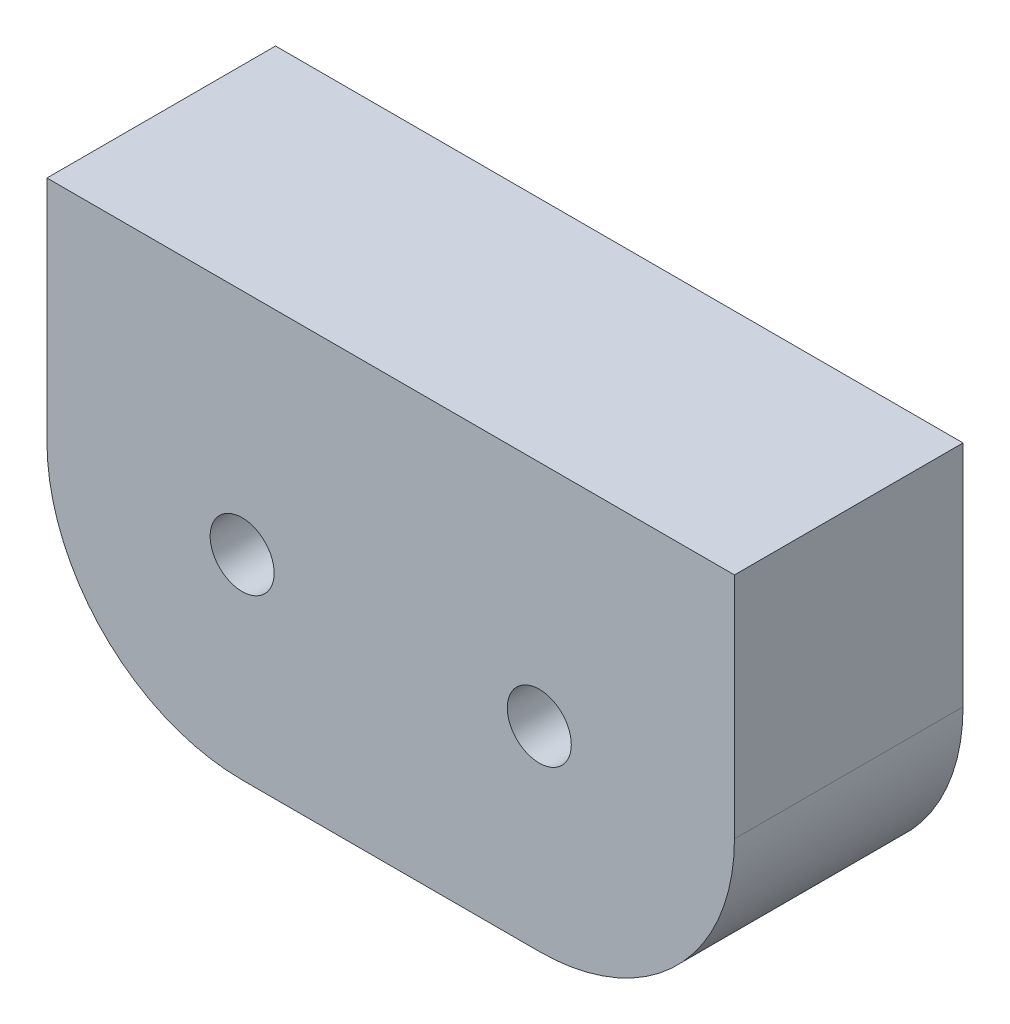
SolidWorks part; units mm, degrees
ref_plane "Front Plane" through (0, 0, 0) normal (0, 0, 1) x (1, 0, 0)
ref_plane "Top Plane" through (0, 0, 0) normal (0, 1, 0) x (1, 0, 0)
ref_plane "Right Plane" through (0, 0, 0) normal (1, 0, 0) x (0, 0, -1)
sketch "Sketch1" plane through (0, 0, 0) normal (0, 0, 1) x (1, 0, 0)
  line L1 (3.25, -1.75) -> (-3.25, -1.75) construction
  line L2 (3.25, -6.0192) -> (-3.25, -6.0192)
  line L4 (-3.25, -6.0192) -> (3.25, -6.0192) construction
  line L5 (7.5192, -1.75) -> (7.5192, 3.25)
  line L6 (7.5192, 3.25) -> (-7.5192, 3.25)
  line L7 (-7.5192, 3.25) -> (-7.5192, -1.75)
  line L8 (-7.5192, -1.75) -> (7.5192, -1.75)
  arc A0 (3.25, -6.0192) -> (7.5192, -1.75) centre (3.25, -1.75) ccw
  arc A1 (-7.5192, -1.75) -> (-3.25, -6.0192) centre (-3.25, -1.75) ccw
  arc A2 (3.25, -6.0192) -> (3.25, 2.5192) centre (3.25, -1.75) ccw construction
  circle A3 centre (0, 33.25) radius 26 construction
  circle A4 centre (-3.25, -1.75) radius 0.7
  circle A5 centre (3.25, -1.75) radius 0.7
  circle A7 centre (-3.25, -1.75) radius 0.7 construction
  point P0 (0, -1.75)
  dimension "D1" = 30
extrude "Boss-Extrude2" add sketch "Sketch1" along normal blind 5 contours A5 L8 A4 A1 L2 A0 | A5 L8 L5 L6 L7 A4
